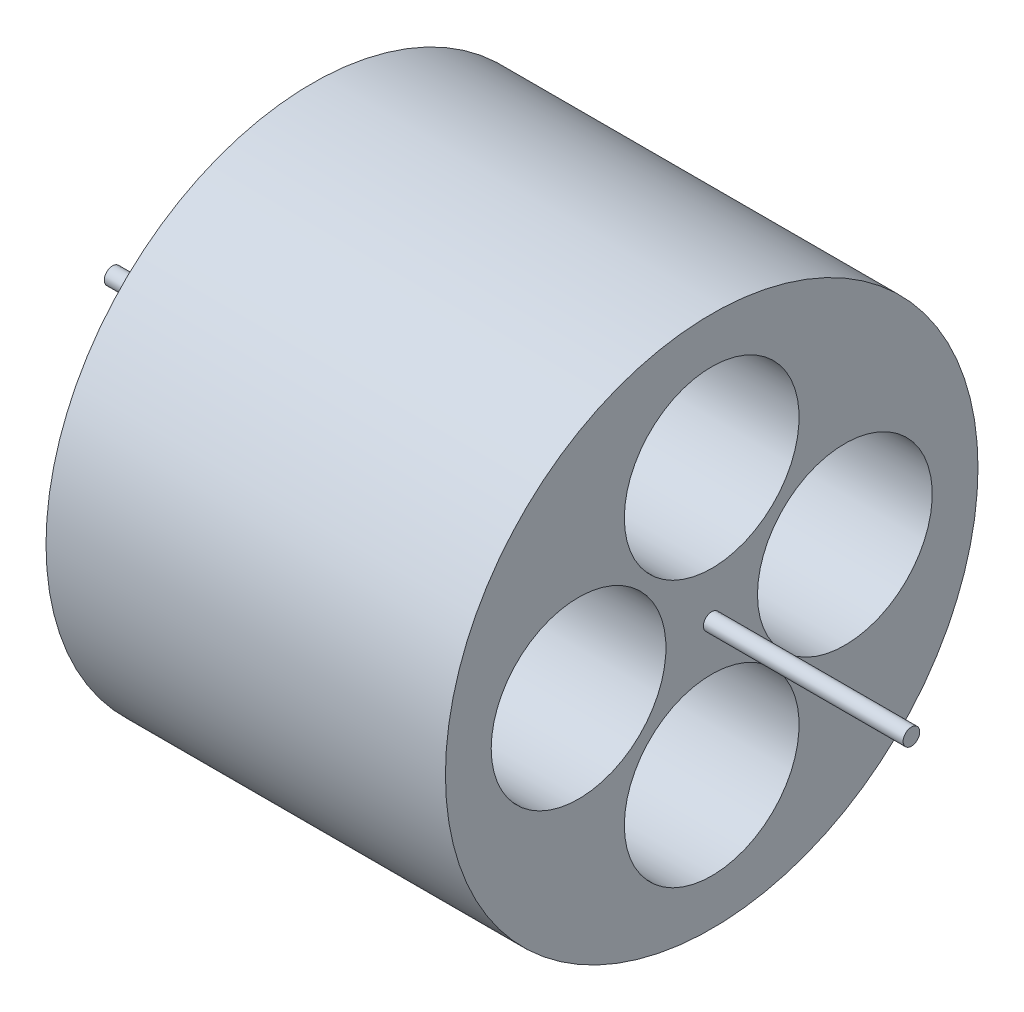
SolidWorks part; units mm, degrees
ref_plane "Front Plane" through (0, 0, 0) normal (0, 0, 1) x (1, 0, 0)
ref_plane "Top Plane" through (0, 0, 0) normal (0, 1, 0) x (1, 0, 0)
ref_plane "Right Plane" through (0, 0, 0) normal (1, 0, 0) x (0, 0, -1)
sketch "Sketch1" plane through (0, 0, 0) normal (1, 0, 0) x (0, 0, -1)
  circle A0 centre (0, 0) radius 101.6
  dimension "D1" = 203.2
extrude "Boss-Extrude1" add sketch "Sketch1" along normal blind 152.4
sketch "Sketch3" plane through (0, 0, 0) normal (1, 0, 0) x (0, 0, -1)
  line L0 (0, 0) -> (101.6, 0) construction
  circle A0 centre (50.8, 0) radius 33.3375
  circle A1 centre (0, 0) radius 101.6 construction
  point P8 (0, 0)
  dimension "D1" = 66.675
extrude "Cut-Extrude1" cut sketch "Sketch3" along normal through all contours A0
sketch "Sketch4" plane through (0, 0, 0) normal (0, 1, 0) x (1, 0, 0)
  line L0 (0, 0) -> (266.5068, 0) construction
pattern_circular "CirPattern1" count 4 over 360 about axis through (0, 0, 0) along (1, 0, 0) of "Cut-Extrude1"
sketch "Sketch2" plane through (0, 0, 0) normal (1, 0, 0) x (0, 0, -1)
  circle A0 centre (0, 0) radius 3.175
  dimension "D1" = 6.35
extrude "Boss-Extrude7" add sketch "Sketch2" against normal blind 76.2 and the other way blind 228.6
